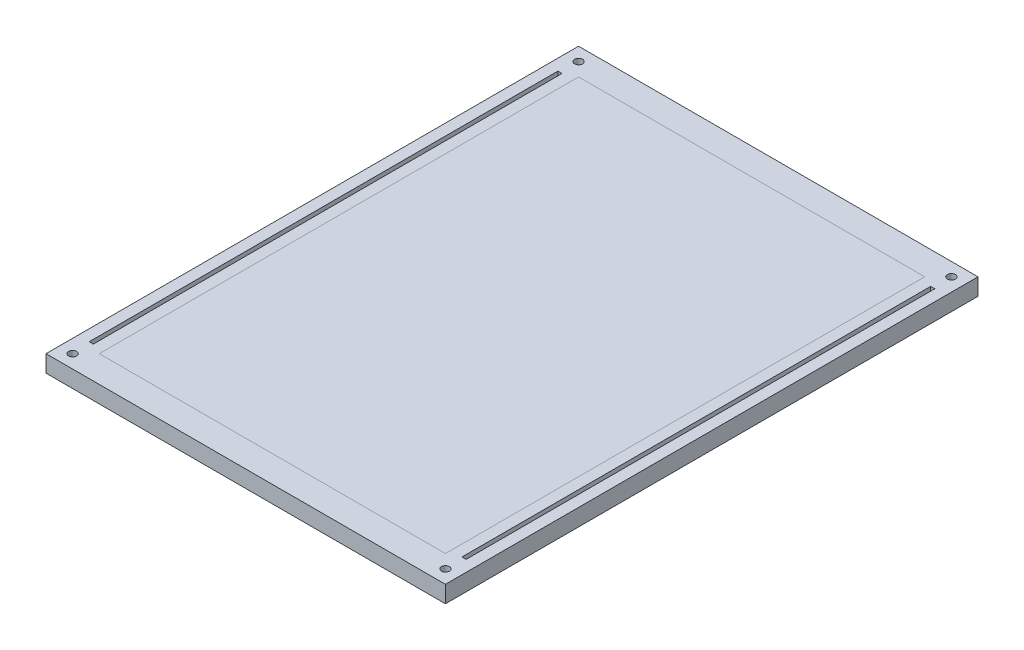
SolidWorks part; units mm, degrees
ref_plane "Front Plane" through (0, 0, 0) normal (0, 0, 1) x (1, 0, 0)
ref_plane "Top Plane" through (0, 0, 0) normal (0, 1, 0) x (1, 0, 0)
ref_plane "Right Plane" through (0, 0, 0) normal (1, 0, 0) x (0, 0, -1)
sketch "Sketch1" plane through (0, 0, 0) normal (0, 1, 0) x (1, 0, 0)
  line L0 (-65, 90) -> (65, 90)
  line L5 (-75, -100) -> (75, -100)
  line L6 (-75, -100) -> (-75, 100)
  line L7 (-75, 100) -> (75, 100)
  line L8 (75, -100) -> (75, 100)
  line L9 (-75, -100) -> (75, 100) construction
  line L10 (-75, 100) -> (75, -100) construction
  line L11 (65, -90) -> (65, 90)
  line L12 (-65, -90) -> (65, -90)
  line L13 (-65, -90) -> (-65, 90)
  line L32 (0, 100) -> (0, -100) construction
  point P0 (0, 0)
  dimension "D2" = 150
  dimension "D3" = 200
  dimension "D1" = 10
extrude "MainBody" add sketch "Sketch1" along normal mid plane 6.35
sketch "Sketch2" plane through (0, 3.175, 0) normal (0, 1, 0) x (1, 0, 0)
  line L0 (-65, 88) -> (-75, 88) construction
  line L4 (-65, 90) -> (-65, -90) construction
  line L10 (-75, 100) -> (-75, -100) construction
  line L11 (-70, 88) -> (-70, 0) construction
  line L12 (65, 90) -> (-65, 90) construction
  line L13 (75, 100) -> (-75, 100) construction
  line L18 (0, 0) -> (0, 100) construction
  line L27 (-70.7779, -88) -> (-69.2221, -88)
  line L28 (-70.7779, -88) -> (-70.7779, 88)
  line L29 (-70.7779, 88) -> (-69.2221, 88)
  line L30 (-69.2221, -88) -> (-69.2221, 88)
  line L31 (-70.7779, -88) -> (-69.2221, 88) construction
  line L32 (-70.7779, 88) -> (-69.2221, -88) construction
  dimension "D1" = 2
  dimension "D2" = 1.5557
extrude "SheetLock" cut sketch "Sketch2" against normal up to next
mirror "Mirror1" about plane through (0, 0, 0) normal (1, 0, 0) of "SheetLock"
sketch "Sketch3" plane through (0, 3.175, 0) normal (0, 1, 0) x (1, 0, 0)
  line L0 (0, 100) -> (0, -100) construction
  line L1 (75, 100) -> (-75, 100) construction
  line L2 (-75, -100) -> (75, -100) construction
  line L3 (-75, 0) -> (75, 0) construction
  line L4 (-75, 100) -> (-75, -100) construction
  line L5 (75, -100) -> (75, 100) construction
  line L6 (-65, 90) -> (-65, 100) construction
  line L7 (-65, 90) -> (-75, 90) construction
  circle A0 centre (-70, 95) radius 1.5
  circle A1 centre (70, 95) radius 1.5
  circle A2 centre (70, -95) radius 1.5
  circle A3 centre (-70, -95) radius 1.5
  point P19 (-65, 95)
  point P20 (-70, 90)
  dimension "D1" = 3
extrude "SupportHoles" cut sketch "Sketch3" against normal up to next
sketch "Sketch4" plane through (65, 0, 0) normal (-1, 0, 0) x (0, 0, 1)
  line L4 (-90, -3.175) -> (90, -3.175)
  line L5 (90, -3.175) -> (90, 3.175)
  line L6 (90, 3.175) -> (-90, 3.175)
  line L7 (-90, 3.175) -> (-90, -3.175)
  line L8 (-90, -3.175) -> (90, -3.175)
  line L9 (90, -3.175) -> (90, 3.175)
  line L10 (90, 3.175) -> (-90, 3.175)
  line L11 (-90, 3.175) -> (-90, -3.175)
  dimension "D1" = 0
extrude "Boss-Extrude1" add sketch "Sketch4" along normal up to surface (130 mm away) separate body up to face at (-65, 0, 0)
equation "\"SheetLockLengthOffset\"=2"
equation "\"SheetThickness\"=0.79375"
equation "\"SheetThicknessTolerance\"= 0.015in"
equation "\"LowerBasketWidth\"=150"
equation "\"D2@Sketch1\"=\"LowerBasketWidth\""
equation "\"LowerBasketLength\"=200"
equation "\"D3@Sketch1\"=\"LowerBasketLength\""
equation "\"SupportHoleDiameter\"=3"
equation "\"D1@Sketch3\"=\"SupportHoleDiameter\""
equation "\"InnerGapOffset\"=10"
equation "\"D1@Sketch1\"=\"InnerGapOffset\""
equation "\"D1@Sketch2\"=\"SheetLockLengthOffset\""
equation "\"D2@Sketch2\"=\"SheetThickness\" + \"SheetThicknessTolerance\"*2"
